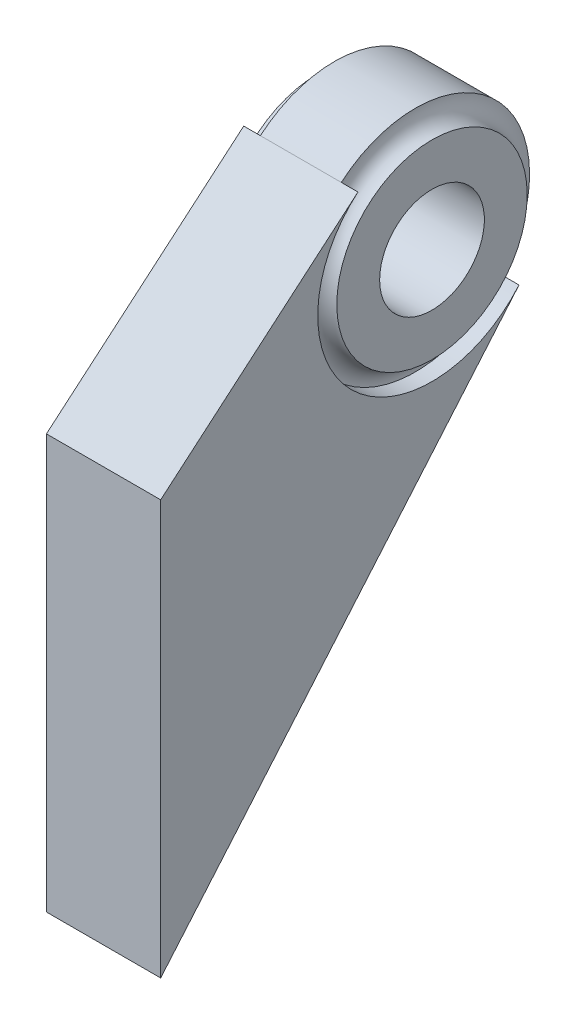
SolidWorks part; units mm, degrees
ref_plane "Front Plane" through (0, 0, 0) normal (0, 0, 1) x (1, 0, 0)
ref_plane "Top Plane" through (0, 0, 0) normal (0, 1, 0) x (1, 0, 0)
ref_plane "Right Plane" through (0, 0, 0) normal (1, 0, 0) x (0, 0, -1)
sketch "Sketch1" plane through (0, 0, 0) normal (1, 0, 0) x (0, 0, -1)
  point P0 (57, 104)
  dimension "D1" = 104
  dimension "D2" = 57
ref_plane "Plane1" through (0, 0, -57) normal (0, 0, 1) x (1, 0, 0)
sketch "Sketch2" plane through (0, 0, -57) normal (0, 0, 1) x (1, 0, 0)
  line L0 (-12, 115) -> (12, 115)
  line L1 (-12, 115) -> (-12, 124)
  line L2 (12, 115) -> (12, 124)
  line L3 (0, 104) -> (0, 140.7685) construction
  line L4 (-8.5, 128) -> (8.5, 128)
  line L5 (-36.0475, 104) -> (43.5223, 104) construction
  arc A0 (-12, 124) -> (-8.5, 128) centre (-12.25, 127.75) ccw
  arc A1 (8.5, 128) -> (12, 124) centre (12.25, 127.75) ccw
  dimension "D1" = 11
  dimension "D2" = 9
  dimension "D3" = 12
  dimension "D4" = 24
  dimension "D5" = 13
  dimension "D6" = 8.5
  dimension "D7" = 17
revolve "Revolve1" add sketch "Sketch2" angle 360 about L5
sketch "Sketch3" plane through (0, 0, 0) normal (1, 0, 0) x (0, 0, -1)
  line L0 (0, 0) -> (0, 87)
  line L1 (0, 87) -> (41.444, 122.276)
  line L2 (0, 0) -> (75.2765, 88.4446)
  circle A0 centre (57, 104) radius 24 construction
  arc A1 (41.444, 122.276) -> (75.2765, 88.4446) centre (57, 104) ccw
  dimension "D1" = 87
extrude "Boss-Extrude1" add sketch "Sketch3" along normal mid plane 24
